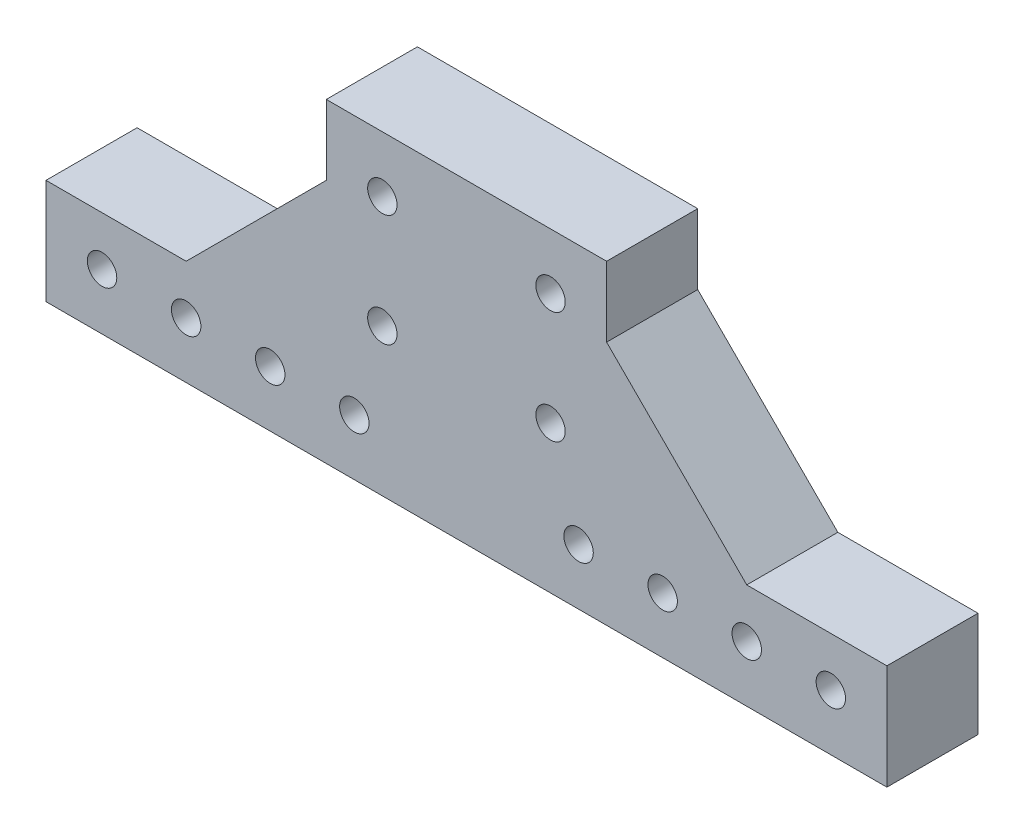
SolidWorks part; units mm, degrees
material "Thornel VCB-20 碳布"
ref_plane "前视基准面" through (0, 0, 0) normal (0, 0, 1) x (1, 0, 0)
ref_plane "上视基准面" through (0, 0, 0) normal (0, 1, 0) x (1, 0, 0)
ref_plane "右视基准面" through (0, 0, 0) normal (1, 0, 0) x (0, 0, -1)
other "Configuration Table"
sketch "草图1" plane through (0, 0, 0) normal (0, 0, 1) x (1, 0, 0)
  line L0 (0, 0) -> (120, 0)
  line L1 (120, 0) -> (120, 15)
  line L2 (120, 15) -> (100, 15)
  line L3 (100, 15) -> (80, 35)
  line L4 (80, 35) -> (80, 45)
  line L5 (80, 45) -> (40, 45)
  line L6 (40, 45) -> (40, 35)
  line L7 (40, 35) -> (20, 15)
  line L8 (20, 15) -> (0, 15)
  line L9 (0, 15) -> (0, 0)
  line L10 (80, 35) -> (80, 15) construction
  line L11 (80, 15) -> (100, 15) construction
  line L12 (40, 35) -> (40, 15) construction
  line L13 (40, 15) -> (20, 15) construction
  dimension "D1" = 135
  dimension "D2" = 135
  dimension "D3" = 40
  dimension "D4" = 15
  dimension "D5" = 30
  dimension "D6" = 40
  dimension "D7" = 20
extrude "凸台-拉伸1" add sketch "草图1" along normal blind 13
sketch "草图2" plane through (0, 0, 13) normal (0, 0, 1) x (1, 0, 0)
  line L0 (8, 8) -> (112, 8) construction
  line L1 (48, 37) -> (48, 21) construction
  line L2 (48, 21) -> (72, 21) construction
  line L3 (72, 21) -> (72, 37) construction
  line L4 (72, 37) -> (48, 37) construction
  line L10 (0, 15) -> (0, 0)
  line L11 (0, 0) -> (120, 0)
  line L12 (120, 0) -> (120, 15)
  line L13 (120, 15) -> (100, 15)
  line L14 (100, 15) -> (80, 35)
  line L15 (80, 35) -> (80, 45)
  line L16 (80, 45) -> (40, 45)
  line L17 (40, 45) -> (40, 35)
  line L18 (40, 35) -> (20, 15)
  line L19 (20, 15) -> (0, 15)
  line L20 (0, 15) -> (0, 0) construction
  line L21 (0, 0) -> (120, 0) construction
  line L22 (120, 0) -> (120, 15) construction
  line L23 (120, 15) -> (100, 15) construction
  line L24 (100, 15) -> (80, 35) construction
  line L25 (80, 35) -> (80, 45) construction
  line L26 (80, 45) -> (40, 45) construction
  line L27 (40, 45) -> (40, 35) construction
  line L28 (40, 35) -> (20, 15) construction
  line L29 (20, 15) -> (0, 15) construction
  circle A0 centre (48, 37) radius 2.1
  circle A1 centre (72, 37) radius 2.1
  circle A2 centre (48, 21) radius 2.1
  circle A3 centre (72, 21) radius 2.1
  circle A4 centre (8, 8) radius 2.1
  circle A5 centre (20, 8) radius 2.1
  circle A6 centre (100, 8) radius 2.1
  circle A7 centre (112, 8) radius 2.1
  dimension "D2" = 4.2
  dimension "D3" = 8
  dimension "D4" = 12
  dimension "D5" = 12
  dimension "D6" = 8
  dimension "D7" = 8
  dimension "D8" = 24
  dimension "D9" = 16
  dimension "D10" = 8
  dimension "D11" = 8
  dimension "D1" = 0
extrude "切除-拉伸1" cut sketch "草图2" against normal blind 3
sketch "草图3" plane through (0, 0, 13) normal (0, 0, 1) x (1, 0, 0)
  line L0 (8, 8) -> (112, 8) construction
  circle A0 centre (32, 8) radius 2.1
  circle A1 centre (44, 8) radius 2.1
  circle A2 centre (76, 8) radius 2.1
  circle A3 centre (88, 8) radius 2.1
  circle A4 centre (20, 8) radius 2.1 construction
  circle A5 centre (100, 8) radius 2.1 construction
  dimension "D1" = 4.2
  dimension "D3" = 12
  dimension "D4" = 12
  dimension "D5" = 12
  dimension "D2" = 12
extrude "切除-拉伸2" cut sketch "草图3" against normal through all
